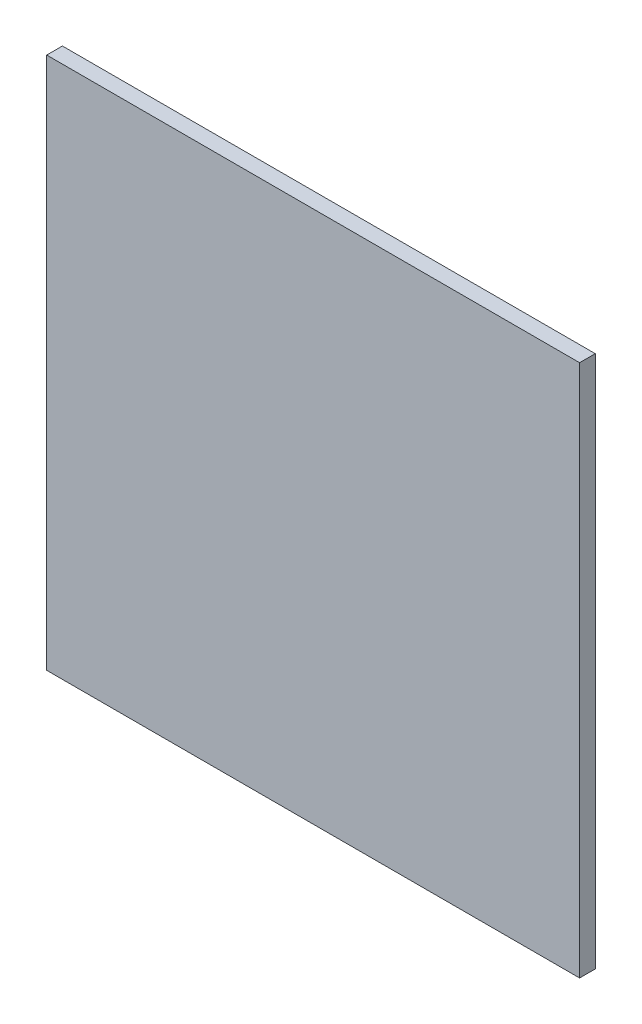
SolidWorks part; units mm, degrees
ref_plane "前视基准面" through (0, 0, 0) normal (0, 0, 1) x (1, 0, 0)
ref_plane "上视基准面" through (0, 0, 0) normal (0, 1, 0) x (1, 0, 0)
ref_plane "右视基准面" through (0, 0, 0) normal (1, 0, 0) x (0, 0, -1)
sketch "草图1" plane through (0, 0, 0) normal (0, 0, 1) x (1, 0, 0)
  line L1 (-51, 51) -> (51, 51)
  line L2 (-51, 51) -> (-51, -51)
  line L3 (-51, -51) -> (51, -51)
  line L4 (51, 51) -> (51, -51)
  line L5 (-51, 51) -> (51, -51) construction
  line L6 (-51, -51) -> (51, 51) construction
  point P0 (0, 0)
  dimension "D1" = 102
  dimension "D2" = 102
extrude "凸台-拉伸1" add sketch "草图1" along normal blind 3
